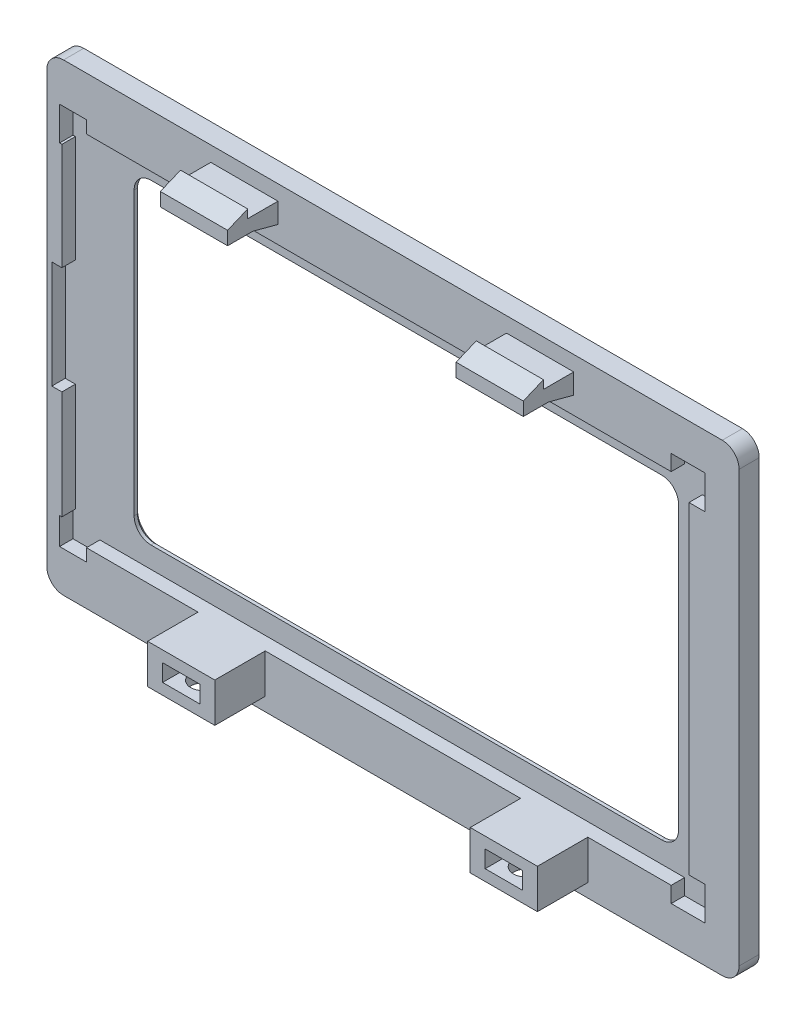
SolidWorks part; units mm, degrees
ref_plane "Front Plane" through (0, 0, 0) normal (0, 0, 1) x (1, 0, 0)
ref_plane "Top Plane" through (0, 0, 0) normal (0, 1, 0) x (1, 0, 0)
ref_plane "Right Plane" through (0, 0, 0) normal (1, 0, 0) x (0, 0, -1)
sketch "Sketch1" plane through (0, 0, 0) normal (0, 0, 1) x (1, 0, 0)
  line L1 (113.8284, 62.9439) -> (10.8284, 62.9439)
  line L2 (113.8284, 62.9439) -> (113.8284, -6.0561)
  line L3 (113.8284, -6.0561) -> (10.8284, -6.0561)
  line L4 (10.8284, 62.9439) -> (10.8284, -6.0561)
  dimension "D1" = 69
  dimension "D2" = 103
extrude "Boss-Extrude1" add sketch "Sketch1" along normal blind 3
sketch "Sketch2" plane through (0, 0, 3) normal (0, 0, 1) x (1, 0, 0)
  line L0 (10.8284, 62.9439) -> (10.8284, -6.0561) construction
  line L1 (21.8284, 51.9439) -> (102.8284, 51.9439)
  line L2 (21.8284, 51.9439) -> (21.8284, 4.9439)
  line L3 (21.8284, 4.9439) -> (102.8284, 4.9439)
  line L4 (102.8284, 51.9439) -> (102.8284, 4.9439)
  line L5 (113.8284, 62.9439) -> (10.8284, 62.9439) construction
  line L6 (113.8284, -6.0561) -> (113.8284, 62.9439) construction
  line L7 (10.8284, -6.0561) -> (113.8284, -6.0561) construction
  dimension "D1" = 11
  dimension "D2" = 11
  dimension "D3" = 11
  dimension "D4" = 11
extrude "Cut-Extrude1" cut sketch "Sketch2" against normal blind 3
sketch "Sketch3" plane through (0, 0, 3) normal (0, 0, 1) x (1, 0, 0)
  line L0 (113.8284, -6.0561) -> (113.8284, 62.9439) construction
  line L1 (13.0784, 55.0939) -> (106.3784, 55.0939)
  line L2 (13.0784, 55.0939) -> (13.0784, 36.0439)
  line L3 (13.0784, 1.7939) -> (106.3784, 1.7939)
  line L11 (106.3784, 55.0939) -> (106.3784, 1.7939)
  line L12 (13.0784, 20.0439) -> (13.0784, 1.7939)
  line L13 (13.0784, 36.0439) -> (11.5784, 36.0439)
  line L15 (13.0784, 20.0439) -> (11.5784, 20.0439)
  line L16 (11.5784, 36.0439) -> (11.5784, 20.0439)
  line L18 (21.8284, 51.9439) -> (21.8284, 4.9439) construction
  point P13 (113.8284, 28.4439)
  point P14 (106.3784, 28.4439)
  dimension "D1" = 93.3
  dimension "D2" = 53.3
  dimension "D3" = 8.75
  dimension "D4" = 1.5
  dimension "D5" = 16
  dimension "D6" = 18.25
extrude "Cut-Extrude2" cut sketch "Sketch3" against normal blind 2
fillet "Fillet2" radius 2.5 4 edges at (113.8284, 62.9439, 1.5) (10.8284, 62.9439, 1.5) (10.8284, -6.0561, 1.5) (113.8284, -6.0561, 1.5)
fillet "Fillet3" radius 2.5 4 edges at (21.8284, 51.9439, 0.5) (21.8284, 4.9439, 0.5) (102.8284, 4.9439, 0.5) (102.8284, 51.9439, 0.5)
chamfer "Chamfer1" distance 0.5 angle 45 8 edges at (62.3284, 4.9439, 0) (102.8284, 28.4439, 0) (62.3284, 51.9439, 0) (21.8284, 28.4439, 0) (102.0961, 51.2116, 0) (102.0961, 5.6761, 0) (22.5606, 51.2116, 0) (22.5606, 5.6761, 0)
sketch "Sketch4" plane through (0, 0, 3) normal (0, 0, 1) x (1, 0, 0)
  line L0 (13.7284, 52.4439) -> (12.7284, 52.4439) construction
  line L1 (16.7284, 55.0939) -> (16.7284, 56.9439)
  line L2 (106.3784, 55.0939) -> (13.0784, 55.0939) construction
  line L4 (16.7284, 55.0939) -> (13.0784, 55.0939)
  line L5 (13.0784, 55.0939) -> (13.0784, 51.9439)
  line L7 (13.0784, 55.0939) -> (13.0784, 36.0439) construction
  line L8 (13.0784, 51.9439) -> (12.7284, 51.9439)
  line L9 (16.7284, 56.9439) -> (12.7284, 56.9439)
  line L10 (12.7284, 56.4439) -> (12.7284, 60.9439) construction
  line L11 (12.7284, 56.9439) -> (12.7284, 51.9439)
  line L12 (16.2284, 56.4439) -> (12.7284, 56.4439) construction
  line L13 (16.2284, 52.4439) -> (16.2284, 56.4439) construction
  line L14 (103.7284, 55.0939) -> (103.7284, 57.4439)
  line L15 (103.7284, 57.4439) -> (108.7284, 57.4439)
  line L16 (108.7284, 57.4439) -> (108.7284, 52.4439)
  line L17 (108.7284, 52.4439) -> (106.3784, 52.4439)
  line L18 (106.3784, 1.7939) -> (106.3784, 55.0939) construction
  line L19 (103.7284, 55.0939) -> (106.3784, 55.0939)
  line L20 (106.3784, 55.0939) -> (106.3784, 52.4439)
  line L21 (104.2284, 56.9439) -> (104.2284, 52.9439) construction
  line L22 (108.2284, 56.9439) -> (104.2284, 56.9439) construction
  line L23 (108.2284, 56.9439) -> (108.2284, 52.9439) construction
  line L24 (108.2284, 52.9439) -> (104.2284, 52.9439) construction
  line L25 (16.7284, 1.7939) -> (16.7284, -0.0561)
  line L26 (13.0784, 1.7939) -> (106.3784, 1.7939) construction
  line L27 (16.7284, -0.0561) -> (12.7284, -0.0561)
  line L28 (12.7284, -4.0561) -> (12.7284, 0.4439) construction
  line L29 (16.7284, 1.7939) -> (13.0784, 1.7939)
  line L30 (13.0784, 1.7939) -> (13.0784, 3.9439)
  line L31 (13.0784, 20.0439) -> (13.0784, 1.7939) construction
  line L32 (13.0784, 3.9439) -> (12.7284, 3.9439)
  line L33 (12.7284, 3.4439) -> (12.7284, 6.9439) construction
  line L34 (12.7284, 3.9439) -> (12.7284, -0.0561)
  line L35 (12.7284, 3.4439) -> (16.2284, 3.4439) construction
  line L36 (16.2284, 3.4439) -> (16.2284, 0.4439) construction
  line L37 (16.2284, 0.4439) -> (12.7284, 0.4439) construction
  line L38 (103.7284, 1.7939) -> (103.7284, -0.5561)
  line L39 (103.7284, -0.5561) -> (108.7284, -0.5561)
  line L40 (108.7284, -0.5561) -> (108.7284, 4.4439)
  line L41 (108.7284, 4.4439) -> (106.3784, 4.4439)
  line L42 (106.3784, 4.4439) -> (106.3784, 1.7939)
  line L43 (106.3784, 1.7939) -> (103.7284, 1.7939)
  line L44 (104.2284, 3.9439) -> (104.2284, -0.0561) construction
  line L45 (108.2284, -0.0561) -> (104.2284, -0.0561) construction
  line L46 (108.2284, 3.9439) -> (108.2284, -0.0561) construction
  line L47 (108.2284, 3.9439) -> (104.2284, 3.9439) construction
  dimension "D1" = 0.5
  dimension "D2" = 0.5
  dimension "D3" = 0.5
  dimension "D4" = 0.5
  dimension "D5" = 0.5
  dimension "D6" = 0.5
  dimension "D7" = 0.5
  dimension "D8" = 0.5
  dimension "D9" = 0.5
  dimension "D10" = 0.5
  dimension "D11" = 0.5
  dimension "D12" = 0.5
  dimension "D13" = 0.5
  dimension "D14" = 0.5
extrude "Cut-Extrude3" cut sketch "Sketch4" against normal up to surface (2 mm away) up to face at (36.0284, 28.2439, 1)
sketch "Sketch5" plane through (0, 0, 3) normal (0, 0, 1) x (1, 0, 0)
  line L1 (79.2284, 60.6939) -> (89.2284, 60.6939)
  line L2 (79.2284, 60.6939) -> (79.2284, 58.6939)
  line L3 (79.2284, 58.6939) -> (89.2284, 58.6939)
  line L4 (89.2284, 60.6939) -> (89.2284, 58.6939)
  line L5 (12.7284, 56.4439) -> (12.7284, 60.9439) construction
  line L6 (35.2284, 60.6939) -> (45.2284, 60.6939)
  line L7 (35.2284, 60.6939) -> (35.2284, 58.6939)
  line L8 (35.2284, 58.6939) -> (45.2284, 58.6939)
  line L9 (45.2284, 60.6939) -> (45.2284, 58.6939)
  line L10 (111.7284, 60.9439) -> (111.7284, -4.0561) construction
  line L12 (12.7284, 60.9439) -> (111.7284, 60.9439) construction
  line L13 (12.7284, 60.9439) -> (111.7284, 60.9439) construction
  dimension "D1" = 2
  dimension "D2" = 10
  dimension "D3" = 22.5
  dimension "D4" = 22.5
  dimension "D5" = 0.25
  dimension "D6" = 0.25
extrude "Boss-Extrude2" add sketch "Sketch5" along normal blind 7.5
sketch "Sketch6" plane through (0, 0, 3) normal (0, 0, 1) x (1, 0, 0)
  line L0 (111.7284, -4.0561) -> (12.7284, -4.0561) construction
  line L5 (111.7284, -4.0561) -> (12.7284, -4.0561) construction
  line L6 (81.3284, -4.0561) -> (91.3284, -4.0561)
  line L7 (81.3284, -4.0561) -> (81.3284, 1.7939)
  line L8 (81.3284, 1.7939) -> (91.3284, 1.7939)
  line L9 (91.3284, -4.0561) -> (91.3284, 1.7939)
  line L10 (16.7284, 1.7939) -> (103.7284, 1.7939) construction
  line L11 (33.3284, -4.0561) -> (43.3284, -4.0561)
  line L13 (33.3284, -4.0561) -> (33.3284, 1.7939)
  line L14 (33.3284, 1.7939) -> (43.3284, 1.7939)
  line L15 (43.3284, -4.0561) -> (43.3284, 1.7939)
  line L16 (10.8284, 60.4439) -> (10.8284, -3.5561) construction
  line L18 (43.3284, 1.7939) -> (81.3284, 1.7939) construction
  line L19 (113.8284, -3.5561) -> (113.8284, 60.4439) construction
  dimension "D1" = 10
  dimension "D2" = 10
  dimension "D3" = 22.5
  dimension "D4" = 22.5
extrude "Boss-Extrude3" add sketch "Sketch6" along normal blind 7.5
sketch "Sketch7" plane through (35.2284, 0, 0) normal (-1, 0, 0) x (0, 0, 1)
  line L0 (7.5, 60.6939) -> (7.5, 61.9439)
  line L1 (10.5, 60.6939) -> (3, 60.6939) construction
  line L2 (7.5, 61.9439) -> (10.5, 60.6939)
  line L3 (7.5, 60.6939) -> (10.5, 60.6939)
  line L4 (3, 57.6939) -> (6.75, 58.6939)
  line L5 (3, 60.4439) -> (3, -3.5561) construction
  line L6 (10.5, 58.6939) -> (3, 58.6939) construction
  line L7 (6.75, 58.6939) -> (3, 58.6939)
  line L8 (3, 58.6939) -> (3, 57.6939)
  dimension "D1" = 3
  dimension "D2" = 1.25
  dimension "D3" = 1
extrude "Boss-Extrude4" add sketch "Sketch7" against normal up to surface (10 mm away) up to face at (45.2284, 59.6939, 6.75)
sketch "Sketch8" plane through (79.2284, 0, 0) normal (-1, 0, 0) x (0, 0, 1)
  line L0 (7.5, 60.6939) -> (7.5, 61.9439)
  line L1 (7.5, 61.9439) -> (10.5, 60.6939)
  line L2 (10.5, 60.6939) -> (7.5, 60.6939)
  line L3 (6.75, 58.6939) -> (3, 58.6939)
  line L4 (3, 60.4439) -> (3, -3.5561) construction
  line L5 (3, 58.6939) -> (3, 57.6939)
  line L6 (3, 57.6939) -> (6.75, 58.6939)
extrude "Boss-Extrude5" add sketch "Sketch8" against normal up to surface (10 mm away) up to face at (89.2284, 59.6939, 6.75)
sketch "Sketch9" plane through (0, 0, 10.5) normal (0, 0, 1) x (1, 0, 0)
  line L0 (38.3284, 1.7939) -> (38.3284, -4.0561) construction
  line L1 (83.5534, -2.4061) -> (89.1034, -2.4061)
  line L2 (83.5534, -2.4061) -> (83.5534, 0.1439)
  line L3 (83.5534, 0.1439) -> (89.1034, 0.1439)
  line L4 (89.1034, -2.4061) -> (89.1034, 0.1439)
  line L5 (35.5534, -2.4061) -> (41.1034, -2.4061)
  line L6 (35.5534, -2.4061) -> (35.5534, 0.1439)
  line L7 (35.5534, 0.1439) -> (41.1034, 0.1439)
  line L8 (41.1034, -2.4061) -> (41.1034, 0.1439)
  line L9 (43.3284, 1.7939) -> (33.3284, 1.7939) construction
  line L10 (33.3284, -4.0561) -> (43.3284, -4.0561) construction
  line L11 (33.3284, -1.1311) -> (43.3284, -1.1311) construction
  line L12 (33.3284, 1.7939) -> (33.3284, -4.0561) construction
  line L13 (43.3284, -4.0561) -> (43.3284, 1.7939) construction
  line L14 (86.3284, 1.7939) -> (86.3284, -4.0561) construction
  line L15 (91.3284, 1.7939) -> (81.3284, 1.7939) construction
  line L16 (81.3284, -4.0561) -> (91.3284, -4.0561) construction
  line L17 (81.3284, -1.1311) -> (91.3284, -1.1311) construction
  line L18 (81.3284, 1.7939) -> (81.3284, -4.0561) construction
  line L19 (91.3284, -4.0561) -> (91.3284, 1.7939) construction
  point P32 (83.5534, -1.1311)
  point P33 (86.3284, 0.1439)
  point P34 (35.5534, -1.1311)
  point P35 (38.3284, 0.1439)
  dimension "D1" = 5.55
  dimension "D2" = 2.55
extrude "Cut-Extrude4" cut sketch "Sketch9" against normal blind 6.5
sketch "Sketch10" plane through (0, -4.0561, 0) normal (0, -1, 0) x (1, 0, 0)
  line L0 (35.5784, 8.7631) -> (35.5784, 5.5877) construction
  line L1 (35.5784, 5.5877) -> (38.3284, 4) construction
  line L2 (38.3284, 4) -> (41.0784, 5.5877) construction
  line L3 (41.0784, 5.5877) -> (41.0784, 8.7631) construction
  line L4 (41.0784, 8.7631) -> (38.3284, 10.3509) construction
  line L5 (38.3284, 10.3509) -> (35.5784, 8.7631) construction
  line L7 (33.3284, 10.5) -> (43.3284, 10.5) construction
  line L10 (35.5784, 7.1754) -> (41.0784, 7.2246) construction
  line L11 (38.3284, 10.3509) -> (38.3284, 4) construction
  line L12 (33.3284, 10.5) -> (33.3284, 3) construction
  line L14 (81.3284, 10.5) -> (81.3284, 3) construction
  line L15 (81.3284, 10.5) -> (91.3284, 10.5) construction
  circle A0 centre (38.3284, 7.2) radius 1.875
  circle A1 centre (86.3284, 7.2) radius 1.875
  point P10 (38.3284, 10.5)
  dimension "D5" = 3.75
  dimension "D6" = 5
  dimension "D7" = 3.3
  dimension "D8" = 5
  dimension "D9" = 3.3
  dimension "D10" = 3.75
  dimension "D1" = 5.5
  dimension "D2" = 5.5
  dimension "D3" = 5.5
  dimension "D4" = 6.5
extrude "Cut-Extrude5" cut sketch "Sketch10" against normal up to surface (1.65 mm away) up to face at (86.3284, -2.4061, 7.25)
